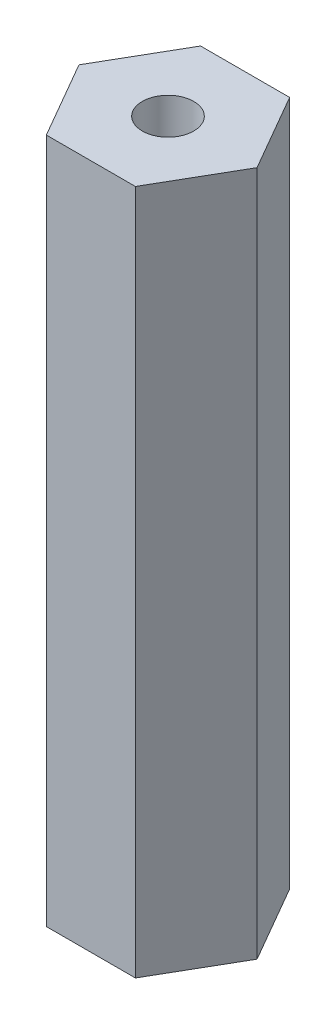
SolidWorks part; units mm, degrees
ref_plane "Alzado" through (0, 0, 0) normal (0, 0, 1) x (1, 0, 0)
ref_plane "Planta" through (0, 0, 0) normal (0, 1, 0) x (1, 0, 0)
ref_plane "Vista lateral" through (0, 0, 0) normal (1, 0, 0) x (0, 0, -1)
sketch "Croquis1" plane through (0, 0, 0) normal (0, 1, 0) x (1, 0, 0)
  line L1 (5.1962, 0) -> (2.5981, 4.5)
  line L2 (2.5981, 4.5) -> (-2.5981, 4.5)
  line L3 (-2.5981, 4.5) -> (-5.1962, 0)
  line L4 (-5.1962, 0) -> (-2.5981, -4.5)
  line L5 (-2.5981, -4.5) -> (2.5981, -4.5)
  line L6 (2.5981, -4.5) -> (5.1962, 0)
  circle A0 centre (0, 0) radius 1.5
  circle A1 centre (0, 0) radius 4.5 construction
  dimension "D1" = 3
  dimension "D2" = 9
extrude "Saliente-Extruir1" add sketch "Croquis1" along normal mid plane 40 contours L5 L6 L1 L2 L3 L4 A0
